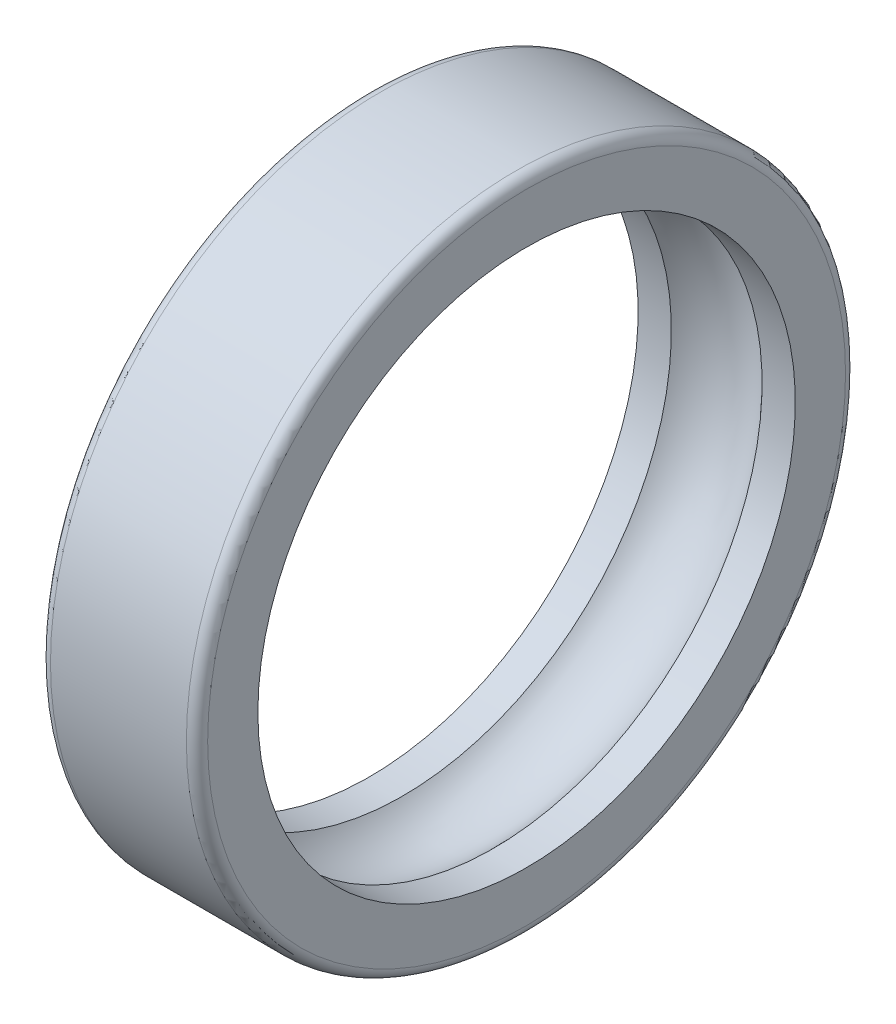
SolidWorks part; units mm, degrees
ref_plane "Front Plane" through (0, 0, 0) normal (0, 0, 1) x (1, 0, 0)
ref_plane "Top Plane" through (0, 0, 0) normal (0, 1, 0) x (1, 0, 0)
ref_plane "Right Plane" through (0, 0, 0) normal (1, 0, 0) x (0, 0, -1)
sketch "Sketch1" plane through (0, 0, 0) normal (0, 0, 1) x (1, 0, 0)
  line L0 (-3.3433, 0) -> (18.1859, 0) construction
  line L1 (-3.3433, 0) -> (-15.5, 0) construction
  line L2 (-15.5, 65) -> (15.5, 65)
  line L3 (-15.5, 65) -> (-15.5, 53)
  line L4 (-15.5, 53) -> (-8.9443, 53)
  line L5 (15.5, 65) -> (15.5, 53)
  line L6 (-15.5, 65) -> (15.5, 53) construction
  line L7 (-15.5, 53) -> (15.5, 65) construction
  line L8 (0, 0) -> (0, 53) construction
  line L9 (8.9443, 53) -> (15.5, 53)
  arc A0 (-8.9443, 53) -> (8.9443, 53) centre (0, 45) cw
  point P3 (0, 59)
  dimension "D5" = 12
  dimension "D1" = 31
  dimension "D2" = 53
  dimension "D3" = 65
  dimension "D4" = 8
revolve "Revolve2" add sketch "Sketch1" angle 360 about L0
fillet "Fillet1" radius 2.1 2 edges at (15.5, 0, 65) (-15.5, 0, 65)
